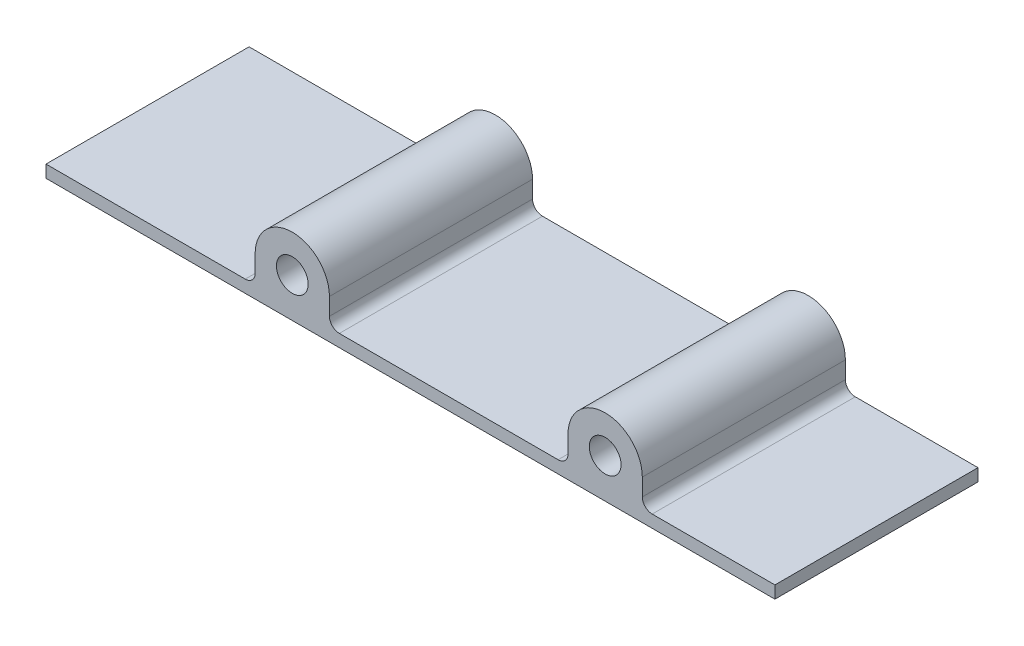
SolidWorks part; units mm, degrees
material "Custom Plastic"
ref_plane "X-Y Datum" through (0, 0, 0) normal (0, 0, 1) x (1, 0, 0)
ref_plane "X-Z Datum" through (0, 0, 0) normal (0, 1, 0) x (1, 0, 0)
ref_plane "Y-Z Datum" through (0, 0, 0) normal (1, 0, 0) x (0, 0, -1)
sketch "Sketch1" plane through (0, 0, 0) normal (0, 0, 1) x (1, 0, 0)
  line L0 (199.6389, 12.4259) -> (199.6389, -12.1414) construction
  line L1 (0, 0) -> (399.2778, 0)
  line L2 (0, 0) -> (0, 3.175)
  line L3 (0, 3.175) -> (399.2778, 3.175)
  line L4 (399.2778, 0) -> (399.2778, 3.175)
extrude "Boss-Extrude1" add sketch "Sketch1" along normal blind 52.1
ref_plane "Plane1" through (399.2778, 0, 52.1) normal (1, 0, 0) x (0, 0, -1)
sketch "Sketch3" plane through (0, 0, 0) normal (0, 0, -1) x (-1, 0, 0)
  line L0 (-303.977, 10.1143) -> (-399.2778, 10.1143) construction
  line L1 (-399.2778, 3.175) -> (0, 3.175) construction
  line L2 (-303.977, 3.175) -> (-303.977, 10.1143) construction
  line L3 (-313.507, 10.1143) -> (-313.507, 3.175)
  line L4 (-294.447, 10.1143) -> (-294.447, 3.175)
  line L5 (-294.447, 3.175) -> (-303.977, 3.175)
  line L6 (-313.507, 3.175) -> (-303.977, 3.175)
  line L7 (-233.243, 3.175) -> (-223.713, 3.175)
  line L8 (-214.183, 3.175) -> (-223.713, 3.175)
  line L9 (-214.183, 10.1143) -> (-214.183, 3.175)
  line L10 (-233.243, 10.1143) -> (-233.243, 3.175)
  line L11 (-152.979, 3.175) -> (-143.449, 3.175)
  line L12 (-133.919, 3.175) -> (-143.449, 3.175)
  line L13 (-133.919, 10.1143) -> (-133.919, 3.175)
  line L14 (-152.979, 10.1143) -> (-152.979, 3.175)
  line L15 (-72.715, 3.175) -> (-63.185, 3.175)
  line L16 (-53.655, 3.175) -> (-63.185, 3.175)
  line L17 (-53.655, 10.1143) -> (-53.655, 3.175)
  line L18 (-72.715, 10.1143) -> (-72.715, 3.175)
  line L19 (-399.2778, 3.175) -> (-303.977, 3.175) construction
  line L20 (-399.2778, 10.1143) -> (-399.2778, 3.175) construction
  circle A0 centre (-303.977, 10.1143) radius 4.075
  arc A1 (-294.447, 10.1143) -> (-313.507, 10.1143) centre (-303.977, 10.1143) ccw
  circle A2 centre (-303.977, 10.1143) radius 9.53 construction
  arc A3 (-214.183, 10.1143) -> (-233.243, 10.1143) centre (-223.713, 10.1143) ccw
  arc A4 (-133.919, 10.1143) -> (-152.979, 10.1143) centre (-143.449, 10.1143) ccw
  arc A5 (-53.655, 10.1143) -> (-72.715, 10.1143) centre (-63.185, 10.1143) ccw
  circle A6 centre (-223.713, 10.1143) radius 4.075
  circle A7 centre (-143.449, 10.1143) radius 4.075
  circle A8 centre (-63.185, 10.1143) radius 4.075
  dimension "D2" = 4
extrude "Boss-Extrude2" add sketch "Sketch3" against normal up to surface (52.1 mm away) up to face at (199.6389, 1.5875, 52.1)
fillet "Fillet1" radius 2.54 8 edges at (53.655, 3.175, 26.05) (72.715, 3.175, 26.05) (133.919, 3.175, 26.05) (152.979, 3.175, 26.05) (214.183, 3.175, 26.05) (233.243, 3.175, 26.05) (294.447, 3.175, 26.05) (313.507, 3.175, 26.05)
sketch "Sketch5" plane through (0, 0, 0) normal (0, 0, -1) x (-1, 0, 0)
  line L6 (-399.2778, 0) -> (-187.0024, 0)
  line L7 (-399.2778, 0) -> (-399.2778, 58.1234)
  line L12 (-399.2778, 58.1234) -> (-187.0024, 58.1234)
  line L13 (-187.0024, 0) -> (-187.0024, 58.1234)
extrude "Cut-Extrude3" cut sketch "Sketch5" against normal through all
